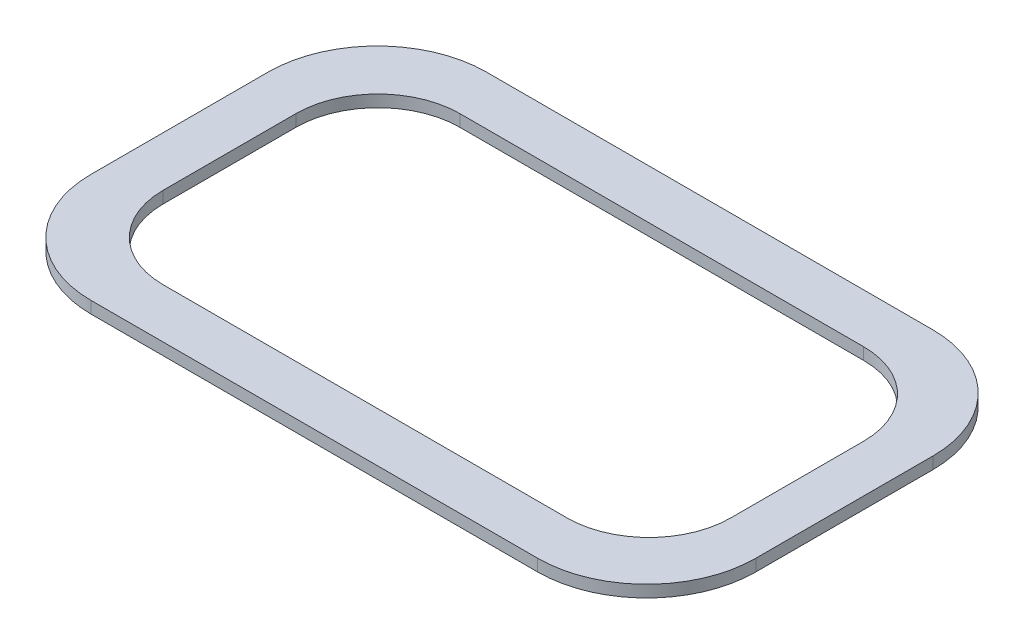
SolidWorks part; units mm, degrees
ref_plane "Front Plane" through (0, 0, 0) normal (0, 0, 1) x (1, 0, 0)
ref_plane "Top Plane" through (0, 0, 0) normal (0, 1, 0) x (1, 0, 0)
ref_plane "Right Plane" through (0, 0, 0) normal (1, 0, 0) x (0, 0, -1)
sketch "Sketch2" plane through (0, 0, 0) normal (0, 1, 0) x (1, 0, 0)
  line L0 (34.7529, -143.1261) -> (192.2601, -143.1261) construction
  line L1 (-21.0438, 31.1339) -> (203.9862, 31.1339)
  line L2 (-76.0438, -23.8661) -> (-76.0438, -113.1261)
  line L3 (-21.0438, -168.1261) -> (203.9862, -168.1261)
  line L4 (258.9862, -23.8661) -> (258.9862, -113.1261)
  line L5 (-9.6667, 6.3189) -> (193.8449, 6.3189)
  line L6 (-50.9167, -34.9311) -> (-50.9167, -101.8761)
  line L7 (-9.6667, -143.1261) -> (193.8449, -143.1261)
  line L8 (235.0949, -34.9311) -> (235.0949, -101.8761)
  arc A0 (-76.0438, -113.1261) -> (-21.0438, -168.1261) centre (-21.0438, -113.1261) ccw
  arc A1 (203.9862, -168.1261) -> (258.9862, -113.1261) centre (203.9862, -113.1261) ccw
  arc A2 (203.9862, 31.1339) -> (258.9862, -23.8661) centre (203.9862, -23.8661) cw
  arc A3 (-21.0438, 31.1339) -> (-76.0438, -23.8661) centre (-21.0438, -23.8661) ccw
  arc A4 (-50.9167, -101.8761) -> (-9.6667, -143.1261) centre (-9.6667, -101.8761) ccw
  arc A5 (193.8449, -143.1261) -> (235.0949, -101.8761) centre (193.8449, -101.8761) ccw
  arc A6 (193.8449, 6.3189) -> (235.0949, -34.9311) centre (193.8449, -34.9311) cw
  arc A7 (-9.6667, 6.3189) -> (-50.9167, -34.9311) centre (-9.6667, -34.9311) ccw
extrude "Boss-Extrude1" add sketch "Sketch2" along normal blind 6
